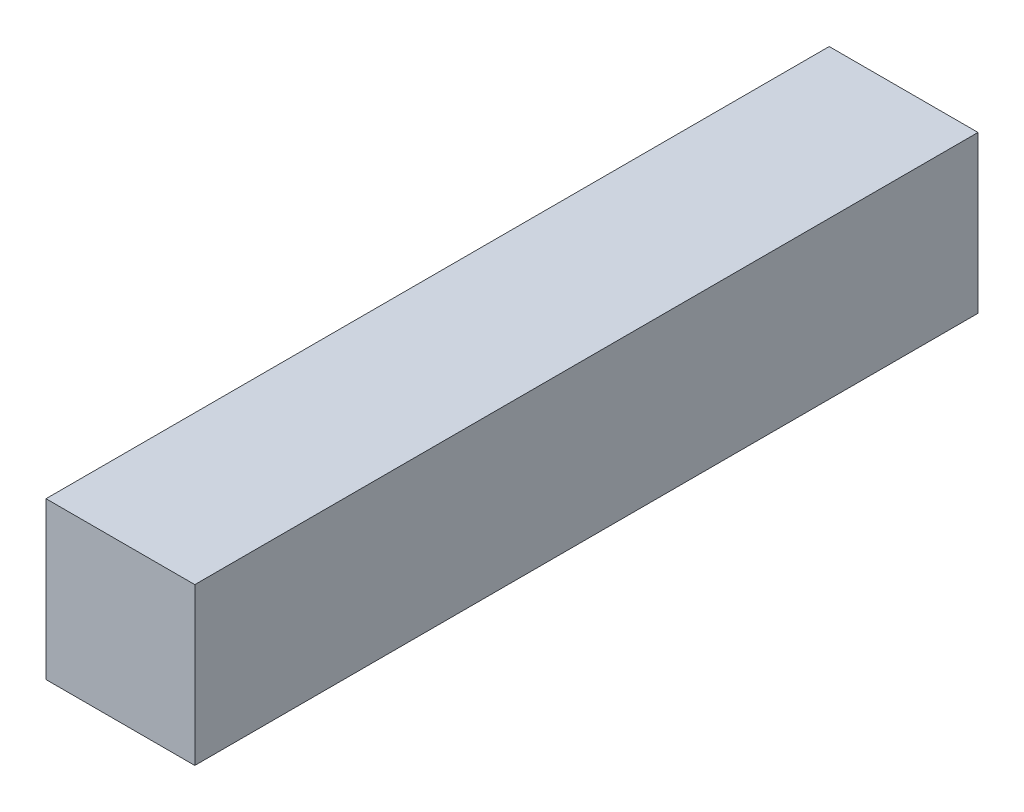
SolidWorks part; units mm, degrees
ref_plane "Front Plane" through (0, 0, 0) normal (0, 0, 1) x (1, 0, 0)
ref_plane "Top Plane" through (0, 0, 0) normal (0, 1, 0) x (1, 0, 0)
ref_plane "Right Plane" through (0, 0, 0) normal (1, 0, 0) x (0, 0, -1)
sketch "Sketch1" plane through (0, 0, 0) normal (0, 0, 1) x (1, 0, 0)
  line L1 (-0.95, 1) -> (0.95, 1)
  line L2 (-0.95, 1) -> (-0.95, -1)
  line L3 (-0.95, -1) -> (0.95, -1)
  line L4 (0.95, 1) -> (0.95, -1)
  line L5 (-0.95, 1) -> (0.95, -1) construction
  line L6 (-0.95, -1) -> (0.95, 1) construction
  point P0 (0, 0)
  dimension "D1" = 2
  dimension "D2" = 1.9
extrude "Boss-Extrude1" add sketch "Sketch1" along normal blind 10
